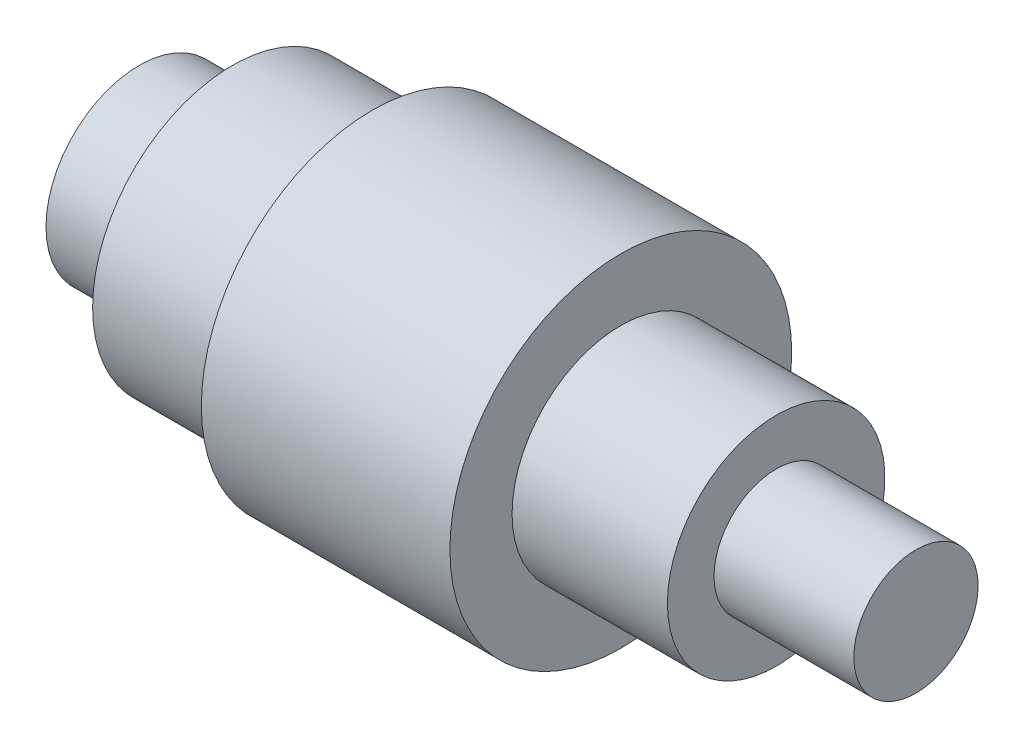
SolidWorks part; units mm, degrees
ref_plane "Plano frontal" through (0, 0, 0) normal (0, 0, 1) x (1, 0, 0)
ref_plane "Plano superior" through (0, 0, 0) normal (0, 1, 0) x (1, 0, 0)
ref_plane "Plano direito" through (0, 0, 0) normal (1, 0, 0) x (0, 0, -1)
sketch "Esboço1" plane through (0, 0, 0) normal (0, 0, 1) x (1, 0, 0)
  line L0 (0, 0) -> (250, 0)
  line L1 (0, 0) -> (0, 30)
  line L2 (0, 30) -> (30, 30)
  line L3 (30, 30) -> (30, 45)
  line L4 (30, 45) -> (75, 45)
  line L5 (75, 45) -> (75, 55)
  line L6 (75, 55) -> (155, 55)
  line L7 (155, 55) -> (155, 35)
  line L8 (155, 35) -> (205, 35)
  line L9 (205, 35) -> (205, 20)
  line L10 (205, 20) -> (250, 20)
  line L11 (250, 20) -> (250, 0)
  point P13 (0, 0)
  point P14 (107.1579, 0)
  point P15 (107.1579, 0)
  point P16 (107.1579, 0)
  point P17 (107.1579, 0)
  dimension "D1" = 250
  dimension "D2" = 30
  dimension "D3" = 45
  dimension "D4" = 80
  dimension "D5" = 50
  dimension "D6" = 30
  dimension "D7" = 45
  dimension "D8" = 55
  dimension "D9" = 20
  dimension "D10" = 35
revolve "Revolução2" add sketch "Esboço1" angle 360 about L0
